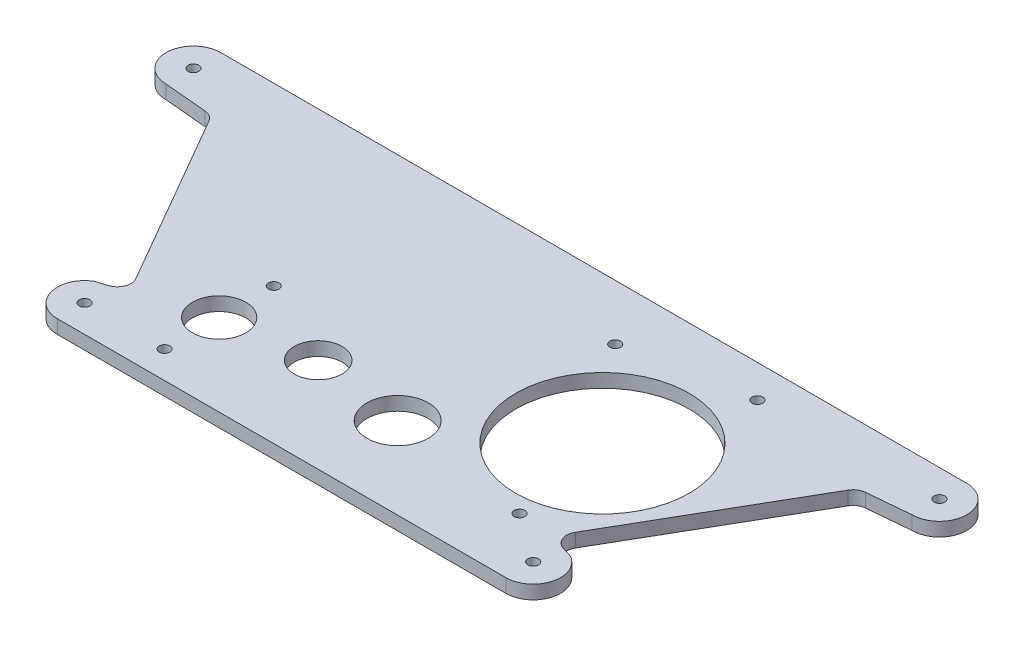
SolidWorks part; units mm, degrees
ref_plane "Front Plane" through (0, 0, 0) normal (0, 0, 1) x (1, 0, 0)
ref_plane "Top Plane" through (0, 0, 0) normal (0, 1, 0) x (1, 0, 0)
ref_plane "Right Plane" through (0, 0, 0) normal (1, 0, 0) x (0, 0, -1)
sketch "Sketch1" plane through (0, 0, 0) normal (0, 1, 0) x (1, 0, 0)
  line L0 (-67.1329, -34.491) -> (-26.9117, -28.6714) construction
  line L1 (-195.4757, -72.591) -> (195.4757, -72.591)
  line L2 (-195.4757, -72.591) -> (-195.4757, 72.591)
  line L3 (-186.1787, 59.891) -> (186.1787, 59.891)
  line L4 (195.4757, -72.591) -> (195.4757, 72.591)
  line L5 (-195.4757, -72.591) -> (195.4757, 72.591) construction
  line L6 (-195.4757, 72.591) -> (195.4757, -72.591) construction
  line L7 (-26.9117, -28.6714) -> (15.8743, -34.491) construction
  line L8 (15.8743, -34.491) -> (-67.1329, -34.491) construction
  line L9 (15.8743, -34.491) -> (72.644, 3.9852) construction
  line L10 (72.644, 3.9852) -> (-26.9117, -28.6714) construction
  line L11 (-166.1463, 72.591) -> (-82.3255, -72.591)
  line L12 (158.814, 72.591) -> (74.9932, -72.591)
  line L13 (-195.4757, 72.591) -> (-180.811, 72.591)
  line L14 (82.3255, -72.591) -> (166.1463, 72.591)
  line L15 (-180.811, 72.591) -> (-96.9902, -72.591) construction
  line L16 (-195.4757, 72.591) -> (-111.6549, -72.591)
  line L17 (96.9902, -72.591) -> (180.811, 72.591) construction
  line L18 (111.6549, -72.591) -> (195.4757, 72.591)
  line L19 (-173.4787, 47.191) -> (-150.2713, 45.0947)
  line L20 (-110.6726, -48.8924) -> (-98.2005, -45.0947)
  line L21 (0, 72.591) -> (0, -72.591) construction
  line L22 (173.4787, 47.191) -> (150.2713, 45.0947)
  line L23 (110.6726, -48.8924) -> (98.2005, -45.0947)
  line L24 (72.644, 3.9852) -> (35.7109, 46.8482) construction
  line L25 (35.7109, 46.8482) -> (91.2979, 57.4018) construction
  line L26 (91.2979, 57.4018) -> (72.644, 3.9852) construction
  line L27 (72.644, 3.9852) -> (81.6718, -43.5654) construction
  line L28 (-173.4787, 72.591) -> (195.4757, 72.591)
  circle A0 centre (-67.1329, -34.491) radius 12.3825
  circle A1 centre (-67.1329, -34.491) radius 32.2072
  circle A2 centre (-67.1329, -9.091) radius 2.4892
  circle A3 centre (-67.1329, -59.891) radius 2.4892
  circle A4 centre (15.8743, -34.491) radius 14.3002
  circle A5 centre (-26.9117, -28.6714) radius 11.1252
  circle A6 centre (72.644, 3.9852) radius 40.3225
  circle A7 centre (-173.4787, 59.891) radius 2.4892
  circle A8 centre (-104.3226, -59.891) radius 2.4892
  circle A9 centre (-173.4787, 59.891) radius 12.7
  circle A10 centre (-104.3226, -59.891) radius 12.7
  circle A11 centre (104.3226, -59.891) radius 2.4892
  circle A12 centre (104.3226, -59.891) radius 12.7
  circle A13 centre (173.4787, 59.891) radius 2.4892
  circle A14 centre (173.4787, 59.891) radius 12.7
  circle A15 centre (35.7109, 46.8482) radius 2.4892
  circle A16 centre (91.2979, 57.4018) radius 2.4892
  circle A17 centre (81.6718, -43.5654) radius 2.4892
  point P0 (0, 0)
  point P16 (-72.4812, -34.491)
  dimension "D1" = 64.4144
  dimension "D2" = 24.765
  dimension "D3" = 4.9784
  dimension "D4" = 25.4
  dimension "D6" = 12.7
  dimension "D11" = 28.6004
  dimension "D14" = 22.2504
  dimension "D15" = 80.645
  dimension "D17" = 50.8
  dimension "D25" = 4.9784
  dimension "D26" = 4.9784
  dimension "D27" = 12.7
  dimension "D28" = 25.4
  dimension "D30" = 25.4
  dimension "D36" = 4.9784
  dimension "D37" = 4.9784
  dimension "D38" = 4.9784
  dimension "D7" = 25.4
  dimension "D8" = 40.64
  dimension "D9" = 43.18
  dimension "D10" = 83.0072
  dimension "D12" = 68.58
  dimension "D13" = 104.775
  dimension "D16" = 120
  dimension "D18" = 120
  dimension "D19" = 12.7
  dimension "D20" = 6.35
  dimension "D21" = 12.7
  dimension "D22" = 12.7
  dimension "D23" = 12.7
  dimension "D24" = 12.7
  dimension "D29" = 31.75
  dimension "D31" = 31.75
  dimension "D32" = 56.58
  dimension "D33" = 48.4
  dimension "D34" = 150
  dimension "D35" = 10.75
  dimension "D39" = 390.9515
  dimension "D40" = 372.3574
  dimension "D41" = 145.1819
  dimension "D42" = 107.0819
  dimension "D43" = 23.3018
  dimension "D44" = 125.161
  dimension "D5" = 2
extrude "Boss-Extrude1" add sketch "Sketch1" along normal blind 6.35 contours L3 A16 L11 A1 A5 L1 L12 A6 A17 A15 A4 | A9 L19 L11 L3 | A9 L3 A7 | L3 A9 A7 | A9 L11 L28 | A9 L3 L11 | L28 L11 L3 L12 | A14 L3 A13 | L22 A14 L3 L14 | L1 L14 L3 L12 | L28 L12 L3 L14 | L3 A14 L14 | L14 A14 L28 | A14 L3 A13 | A12 L23 A11 | L14 A12 L23 | L1 A12 L14 | A5 A1 A3 A2 A0 | A10 L20 A8 | A10 L1 L11 | A10 L11 L20
sketch "Sketch2" plane through (0, 6.35, 0) normal (0, 1, 0) x (1, 0, 0)
  line L0 (-150.2713, 45.0947) -> (-98.2005, -45.0947)
  line L1 (-158.814, 72.591) -> (-74.9932, -72.591)
  line L2 (-173.4787, 72.591) -> (173.4787, 72.591) construction
  line L3 (-104.3226, -72.591) -> (104.3226, -72.591) construction
  line L4 (-155.1478, 66.241) -> (155.1478, 66.241)
  line L5 (-78.6593, -66.241) -> (78.6593, -66.241)
  line L6 (150.2713, 45.0947) -> (98.2005, -45.0947)
  line L7 (158.814, 72.591) -> (74.9932, -72.591)
  line L8 (-26.9117, -28.6714) -> (-26.9117, 66.241) construction
  line L9 (-26.9117, -28.6714) -> (15.8743, -34.491) construction
  line L10 (15.8743, -34.491) -> (72.644, 3.9852) construction
  line L11 (35.7109, 46.8482) -> (35.7109, 66.241) construction
  line L12 (15.8743, -34.491) -> (15.8743, -66.241) construction
  line L13 (-67.1329, -9.091) -> (-110.6258, 66.241) construction
  line L14 (-143.9514, 46.8482) -> (35.7109, 46.8482) construction
  line L15 (-26.9117, -28.6714) -> (-3.1757, -59.7979) construction
  line L16 (-145.7845, 50.0232) -> (23.4142, 50.0232)
  line L17 (-142.1183, 43.6732) -> (23.4142, 43.6732)
  line L18 (-114.292, 66.241) -> (-77.5651, 2.6281)
  line L19 (-106.9596, 66.241) -> (-70.9535, 3.8765)
  line L20 (-30.0867, 66.241) -> (-30.0867, -11.487)
  line L21 (-23.7367, 66.241) -> (-23.7367, -11.487)
  line L22 (-19.0162, -44.2612) -> (-13.1568, -51.9451)
  line L23 (-8.1074, -48.0946) -> (-13.9669, -40.4108)
  line L24 (-9.4562, -27.8414) -> (-3.9163, -28.5949)
  line L25 (-10.3121, -34.1334) -> (-4.7721, -34.887)
  line L26 (12.6993, -54.8956) -> (12.6993, -66.241)
  line L27 (19.0493, -54.8956) -> (19.0493, -66.241)
  line L28 (30.9837, -20.4149) -> (32.3173, -19.5111)
  line L29 (34.5464, -25.6713) -> (35.8799, -24.7675)
  line L30 (32.5359, 59.145) -> (32.5359, 66.241)
  line L31 (38.8859, 59.145) -> (38.8859, 66.241)
  line L32 (36.5245, 66.241) -> (36.5245, -72.591) construction
  line L33 (30.1745, 66.241) -> (30.1745, -72.591) construction
  line L34 (30.1745, -19.5935) -> (-23.7367, 66.241) construction
  line L35 (18.2805, -13.9814) -> (-32.1059, 66.241) construction
  line L36 (-17.9315, 43.6732) -> (18.2805, -13.9814)
  line L37 (0.1745, 14.8459) -> (-23.7367, -0.1724) construction
  line L38 (-1.8899, 13.5493) -> (-1.8899, 66.241) construction
  line L39 (-1.8899, 13.5493) -> (-26.9117, -28.6714) construction
  line L40 (-1.8899, 13.5493) -> (15.8743, -34.491) construction
  line L41 (-5.0649, 66.241) -> (-5.0649, 22.5296)
  line L42 (1.2851, 66.241) -> (1.2851, 22.5296)
  line L43 (-9.1997, 7.4426) -> (-20.8819, -12.2694)
  line L44 (-3.737, 4.2051) -> (-15.4192, -15.5069)
  line L45 (-1.7532, 4.0253) -> (5.8195, -16.454)
  line L46 (4.2026, 6.2276) -> (11.7754, -14.2517)
  circle A0 centre (-67.1329, -34.491) radius 38.5572
  circle A1 centre (72.644, 3.9852) radius 46.6725
  circle A2 centre (-26.9117, -28.6714) radius 17.4752
  circle A3 centre (15.8743, -34.491) radius 20.6502
  circle A4 centre (35.7109, 46.8482) radius 12.7
  circle A5 centre (91.2979, 57.4018) radius 12.7
  circle A6 centre (81.6718, -43.5654) radius 12.7
  circle A7 centre (-99.4294, 46.8482) radius 2.1526
  circle A8 centre (-26.9117, 46.8482) radius 2.1527
  circle A9 centre (-99.4294, 46.8482) radius 9.525
  circle A10 centre (-26.9117, 46.8482) radius 9.525
  circle A11 centre (-3.1757, -59.7979) radius 12.7
  circle A12 centre (-3.1757, -59.7979) radius 2.1527
  circle A13 centre (-1.8899, 13.5493) radius 9.525
  circle A14 centre (-1.8899, 13.5493) radius 2.1526
  point P96 (-17.9315, 43.6732)
  dimension "D1" = 77.1144
  dimension "D4" = 93.345
  dimension "D7" = 34.9504
  dimension "D8" = 41.3004
  dimension "D9" = 25.4
  dimension "D10" = 25.4
  dimension "D11" = 25.4
  dimension "D12" = 4.3053
  dimension "D13" = 4.3053
  dimension "D14" = 19.05
  dimension "D15" = 19.05
  dimension "D17" = 25.4
  dimension "D18" = 4.3053
  dimension "D28" = 75.5196
  dimension "D31" = 19.05
  dimension "D35" = 4.3053
  dimension "D2" = 6.35
  dimension "D3" = 6.35
  dimension "D5" = 6.35
  dimension "D6" = 6.35
  dimension "D16" = 19.05
  dimension "D19" = 12.793
  dimension "D20" = 6.35
  dimension "D21" = 6.35
  dimension "D22" = 6.35
  dimension "D23" = 6.35
  dimension "D24" = 6.35
  dimension "D25" = 6.35
  dimension "D26" = 6.35
  dimension "D27" = 6.35
  dimension "D29" = 1.7536
  dimension "D30" = 6.35
  dimension "D32" = 6.35
  dimension "D33" = 6.35
  dimension "D34" = 6.35
extrude "Cut-Extrude1" [suppressed] cut sketch "Sketch2" against normal through all contours A9 L17 L1 A0 L18 | A9 L18 L4 L1 L16 | A10 L20 L4 L19 A9 L16 | A10 L17 A9 L19 A0 A2 L20 | A10 L21 A2 L24 A3 L28 A1 A4 L17 | A5 L4 L31 A4 A1 | A5 A1 L7 L4 | A6 A1 L29 A3 L27 L5 L7 | A11 L22 A2 A0 L5 | A7 | A8 | A12 | A10 L16 L41 L4 L21 | L41 L17 L36 | A13 L41 L36 A10 L21 A2 L43 | A13 L44 A2 L24 A3 L45 | A13 L46 A3 L36 | A4 L30 L4 L42 L16 | A14
fillet "Fillet1" [suppressed] radius 2.54
fillet "Fillet2" radius 6.35 4 edges at (-98.2005, 3.175, 45.0947) (98.2005, 3.175, 45.0947) (150.2713, 3.175, -45.0947) (-150.2713, 3.175, -45.0947)
